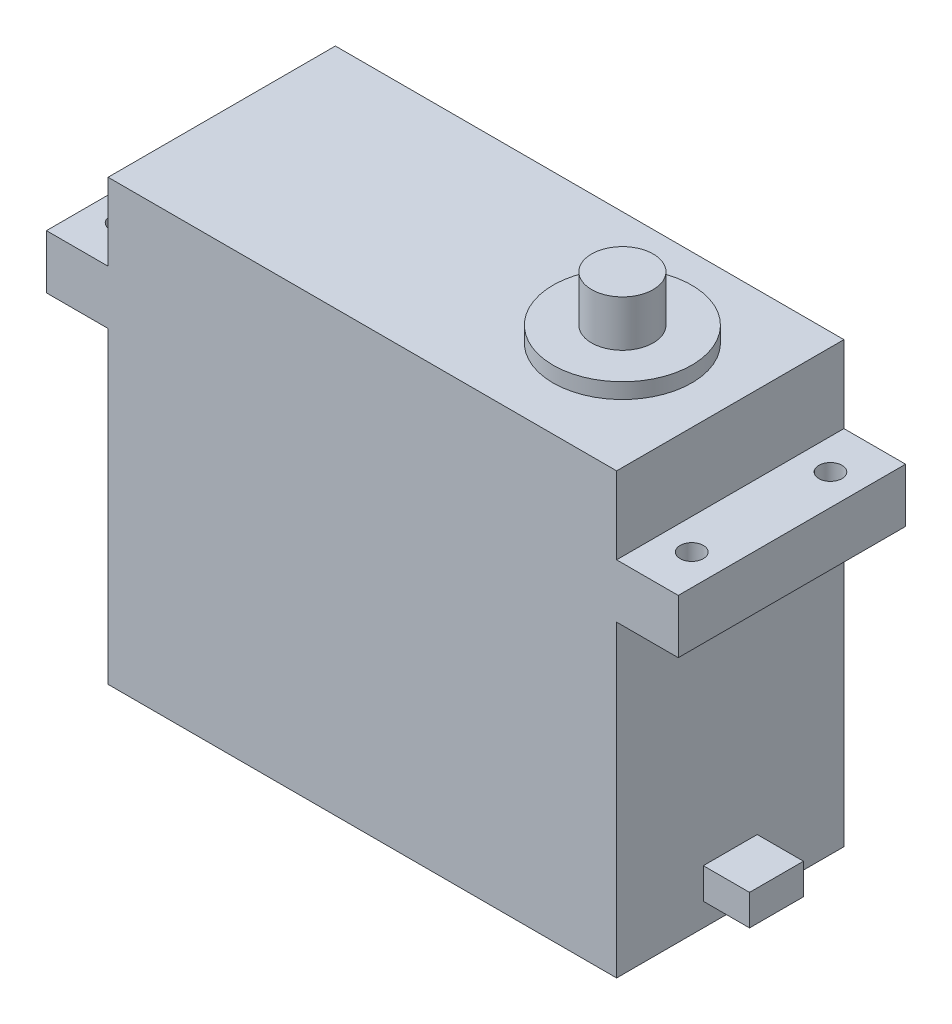
SolidWorks part; units mm, degrees
material "ABS"
ref_plane "Plan de face" through (0, 0, 0) normal (0, 0, 1) x (1, 0, 0)
ref_plane "Plan de dessus" through (0, 0, 0) normal (0, 1, 0) x (1, 0, 0)
ref_plane "Plan de droite" through (0, 0, 0) normal (1, 0, 0) x (0, 0, -1)
sketch "Esquisse1" plane through (0, 0, 0) normal (0, 1, 0) x (1, 0, 0)
  line L0 (0, 0) -> (14, 0) construction
  line L1 (-52, 14.75) -> (14, 14.75)
  line L2 (-52, 14.75) -> (-52, -14.75)
  line L3 (-52, -14.75) -> (14, -14.75)
  line L4 (14, 14.75) -> (14, -14.75)
  dimension "D1" = 66
  dimension "D2" = 29.5
  dimension "D3" = 14
extrude "Boss.-Extru.1" add sketch "Esquisse1" along normal blind 57
sketch "Esquisse2" plane through (0, 57, 0) normal (0, 1, 0) x (1, 0, 0)
  circle A0 centre (0, 0) radius 9
  dimension "D1" = 18
extrude "Boss.-Extru.2" add sketch "Esquisse2" along normal blind 2
sketch "Esquisse3" plane through (0, 59, 0) normal (0, 1, 0) x (1, 0, 0)
  circle A0 centre (0, 0) radius 4
  dimension "D1" = 8
extrude "Boss.-Extru.3" add sketch "Esquisse3" along normal blind 6
sketch "Esquisse4" plane through (0, 0, 0) normal (0, 1, 0) x (1, 0, 0)
  line L0 (-52, -14.75) -> (14, -14.75) construction
  line L1 (-60, -14.75) -> (22, -14.75)
  line L2 (-60, -14.75) -> (-60, 14.75)
  line L3 (-60, 14.75) -> (22, 14.75)
  line L4 (22, -14.75) -> (22, 14.75)
  line L5 (14, 14.75) -> (-52, 14.75) construction
  line L6 (-60, 0) -> (-19, 0) construction
  line L7 (-19, 0) -> (-19, 14.75) construction
  circle A0 centre (-56, 9) radius 1.5
  circle A1 centre (-56, -9) radius 1.5
  circle A2 centre (18, -9) radius 1.5
  circle A3 centre (18, 9) radius 1.5
  point P6 (-19, 14.75)
  dimension "D2" = 18
  dimension "D3" = 74
  dimension "D4" = 3
  dimension "D1" = 82
extrude "Boss.-Extru.4" add sketch "Esquisse4" along normal blind 7 from offset 40
sketch "Esquisse5" plane through (14, 0, 0) normal (1, 0, 0) x (0, 0, -1)
  line L0 (0, 3) -> (0, 0) construction
  line L1 (-3.5, 7) -> (3.5, 7)
  line L2 (-3.5, 7) -> (-3.5, 3)
  line L3 (-3.5, 3) -> (3.5, 3)
  line L4 (3.5, 7) -> (3.5, 3)
  line L5 (-14.75, 0) -> (14.75, 0) construction
  dimension "D1" = 3
  dimension "D2" = 4
  dimension "D3" = 7
extrude "Boss.-Extru.5" add sketch "Esquisse5" along normal blind 6
